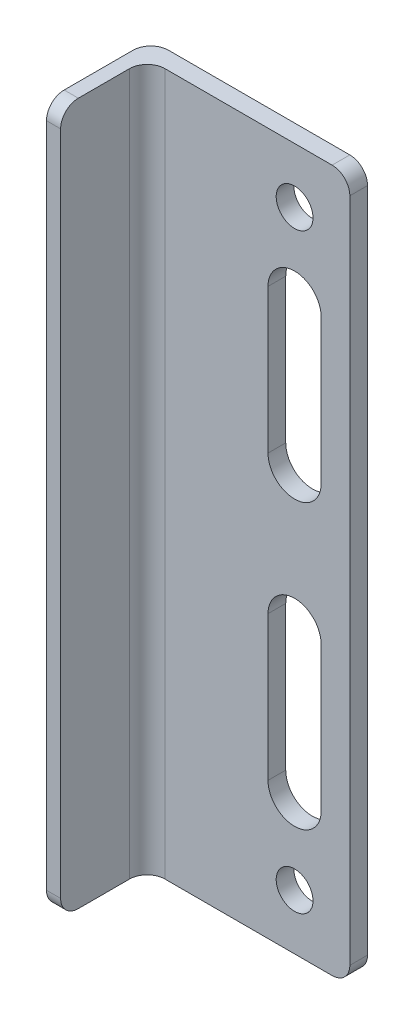
SolidWorks part; units mm, degrees
material "AISI 4130 Steel, annealed at 865C"
ref_plane "X-Y Datum" through (0, 0, 0) normal (0, 0, 1) x (1, 0, 0)
ref_plane "X-Z Datum" through (0, 0, 0) normal (0, 1, 0) x (1, 0, 0)
ref_plane "Y-Z Datum" through (0, 0, 0) normal (1, 0, 0) x (0, 0, -1)
sketch "Sketch1" plane through (0, 0, 0) normal (0, 0, 1) x (1, 0, 0)
  line L1 (9.9, -62.9) -> (-9.9, -62.9)
  line L2 (9.9, -62.9) -> (9.9, 62.9)
  line L3 (9.9, 62.9) -> (-9.9, 62.9)
  line L4 (-9.9, -62.9) -> (-9.9, 62.9)
  line L5 (0, -53) -> (0, 53) construction
  line L7 (-9.9, 62.9) -> (-28.95, 62.9)
  line L8 (-9.9, 62.9) -> (-9.9, -62.9)
  line L9 (-9.9, -62.9) -> (-28.95, -62.9)
  line L10 (-28.95, 62.9) -> (-28.95, -62.9)
  circle A0 centre (0, 53) radius 3.3
  circle A1 centre (0, -53) radius 3.3
  point P4 (0, 62.9)
  point P5 (-9.9, 0)
  point P10 (0, 0)
  dimension "D1" = 6.6
  dimension "D2" = 9.9
  dimension "D3" = 106
  dimension "D4" = 9.9
  dimension "D5" = 19.05
extrude "Boss-Extrude1" add sketch "Sketch1" along normal blind 3.175
sketch "Sketch6" plane through (0, 0, 3.175) normal (0, 0, 1) x (1, 0, 0)
  line L0 (0, 38.3375) -> (0, 12.4625) construction
  line L1 (4.7625, 38.3375) -> (4.7625, 12.4625)
  line L2 (-4.7625, 38.3375) -> (-4.7625, 12.4625)
  line L3 (0, -12.4625) -> (0, -38.3375) construction
  line L4 (4.7625, -12.4625) -> (4.7625, -38.3375)
  line L5 (-4.7625, -12.4625) -> (-4.7625, -38.3375)
  line L6 (0, 53) -> (0, 0) construction
  line L8 (9.9, 62.9) -> (-28.95, 62.9) construction
  arc A0 (4.7625, 38.3375) -> (-4.7625, 38.3375) centre (0, 38.3375) ccw
  arc A1 (-4.7625, 12.4625) -> (4.7625, 12.4625) centre (0, 12.4625) ccw
  arc A2 (4.7625, -12.4625) -> (-4.7625, -12.4625) centre (0, -12.4625) ccw
  arc A3 (-4.7625, -38.3375) -> (4.7625, -38.3375) centre (0, -38.3375) ccw
  circle A5 centre (0, 53) radius 9.9 construction
  circle A6 centre (0, 53) radius 3.3 construction
  point P3 (0, 25.4)
  point P10 (0, -25.4)
  dimension "D2" = 9.525
  dimension "D3" = 25.4
  dimension "D4" = 25.4
extrude "Cut-Extrude1" cut sketch "Sketch6" against normal through all both and the other way through all
fillet "Fillet1" radius 3.175 2 edges at (9.9, -62.9, 1.5875) (9.9, 62.9, 1.5875)
sketch "Sketch7" plane through (0, 0, 3.175) normal (0, 0, 1) x (1, 0, 0)
  line L0 (-28.95, 62.9) -> (-28.95, -62.9) construction
  line L1 (-28.95, 62.9) -> (-28.95, -62.9)
extrude "Extrude-Thin1" add sketch "Sketch7" along normal blind 15.5252 thin thin type one direction reverse wall 2.54
fillet "Fillet2" radius 3.175 4 edges at (-27.68, -62.9, 18.7002) (-27.68, 62.9, 18.7002) (-28.95, 0, 0) (-26.41, 0, 3.175)
